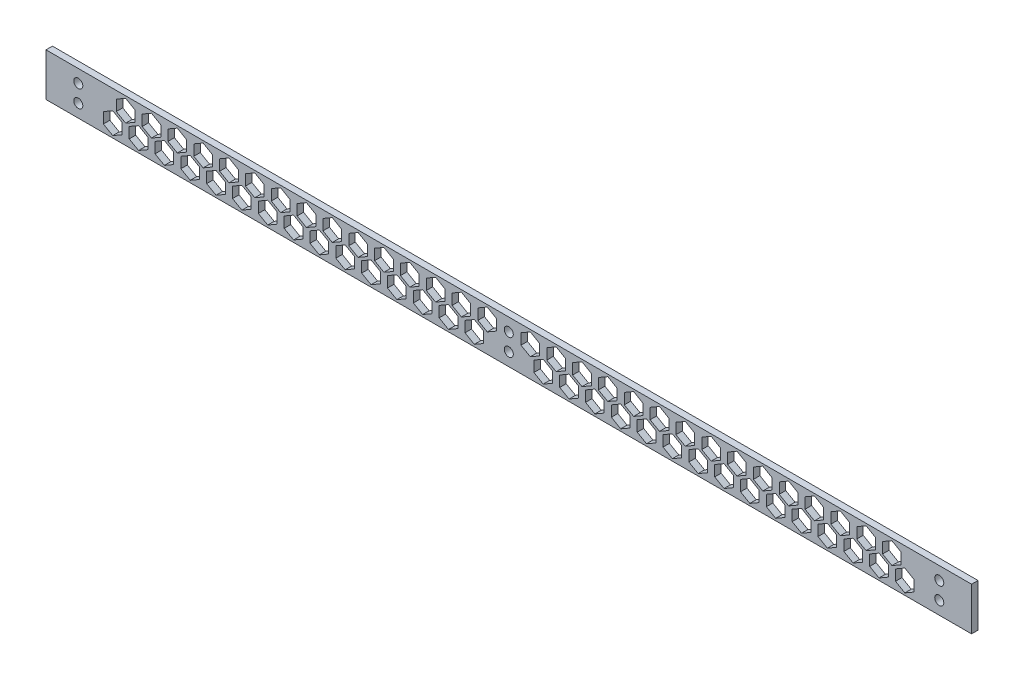
SolidWorks part; units mm, degrees
ref_plane "前视基准面" through (0, 0, 0) normal (0, 0, 1) x (1, 0, 0)
ref_plane "上视基准面" through (0, 0, 0) normal (0, 1, 0) x (1, 0, 0)
ref_plane "右视基准面" through (0, 0, 0) normal (1, 0, 0) x (0, 0, -1)
other "Configuration Table"
sketch "草图2" plane through (0, 0, 0) normal (0, 0, 1) x (1, 0, 0)
  line L0 (0, 42.2596) -> (0, -23.9078) construction
  line L1 (215, -10) -> (-215, -10)
  line L2 (215, -10) -> (215, 10)
  line L3 (215, 10) -> (-215, 10)
  line L4 (-215, -10) -> (-215, 10)
  line L5 (215, -10) -> (-215, 10) construction
  line L6 (215, 10) -> (-215, -10) construction
  line L7 (-28, -9) -> (-23.6699, -6.5)
  line L8 (-10, 9) -> (-14.3301, 6.5)
  line L9 (-14.3301, 6.5) -> (-14.3301, 1.5)
  line L10 (-14.3301, 1.5) -> (-10, -1)
  line L11 (-10, -1) -> (-5.6699, 1.5)
  line L12 (-5.6699, 1.5) -> (-5.6699, 6.5)
  line L13 (-5.6699, 6.5) -> (-10, 9)
  line L14 (-16, -9) -> (-11.6699, -6.5)
  line L15 (-11.6699, -6.5) -> (-11.6699, -1.5)
  line L16 (-11.6699, -1.5) -> (-16, 1)
  line L17 (-16, 1) -> (-20.3301, -1.5)
  line L18 (-20.3301, -1.5) -> (-20.3301, -6.5)
  line L19 (-20.3301, -6.5) -> (-16, -9)
  line L20 (-23.6699, -6.5) -> (-23.6699, -1.5)
  line L21 (-23.6699, -1.5) -> (-28, 1)
  line L22 (-28, 1) -> (-32.3301, -1.5)
  line L23 (-32.3301, -1.5) -> (-32.3301, -6.5)
  line L24 (-32.3301, -6.5) -> (-28, -9)
  line L25 (-22, 9) -> (-26.3301, 6.5)
  line L26 (-26.3301, 6.5) -> (-26.3301, 1.5)
  line L27 (-26.3301, 1.5) -> (-22, -1)
  line L28 (-22, -1) -> (-17.6699, 1.5)
  line L29 (-17.6699, 1.5) -> (-17.6699, 6.5)
  line L30 (-17.6699, 6.5) -> (-22, 9)
  line L31 (-40, -9) -> (-35.6699, -6.5)
  line L32 (-35.6699, -6.5) -> (-35.6699, -1.5)
  line L33 (-35.6699, -1.5) -> (-40, 1)
  line L34 (-40, 1) -> (-44.3301, -1.5)
  line L35 (-44.3301, -1.5) -> (-44.3301, -6.5)
  line L36 (-44.3301, -6.5) -> (-40, -9)
  line L37 (-34, 9) -> (-38.3301, 6.5)
  line L38 (-38.3301, 6.5) -> (-38.3301, 1.5)
  line L39 (-38.3301, 1.5) -> (-34, -1)
  line L40 (-34, -1) -> (-29.6699, 1.5)
  line L41 (-29.6699, 1.5) -> (-29.6699, 6.5)
  line L42 (-29.6699, 6.5) -> (-34, 9)
  line L43 (-52, -9) -> (-47.6699, -6.5)
  line L44 (-47.6699, -6.5) -> (-47.6699, -1.5)
  line L45 (-47.6699, -1.5) -> (-52, 1)
  line L46 (-52, 1) -> (-56.3301, -1.5)
  line L47 (-56.3301, -1.5) -> (-56.3301, -6.5)
  line L48 (-56.3301, -6.5) -> (-52, -9)
  line L49 (-46, 9) -> (-50.3301, 6.5)
  line L50 (-50.3301, 6.5) -> (-50.3301, 1.5)
  line L51 (-50.3301, 1.5) -> (-46, -1)
  line L52 (-46, -1) -> (-41.6699, 1.5)
  line L53 (-41.6699, 1.5) -> (-41.6699, 6.5)
  line L54 (-41.6699, 6.5) -> (-46, 9)
  line L55 (-64, -9) -> (-59.6699, -6.5)
  line L56 (-59.6699, -6.5) -> (-59.6699, -1.5)
  line L57 (-59.6699, -1.5) -> (-64, 1)
  line L58 (-64, 1) -> (-68.3301, -1.5)
  line L59 (-68.3301, -1.5) -> (-68.3301, -6.5)
  line L60 (-68.3301, -6.5) -> (-64, -9)
  line L61 (-58, 9) -> (-62.3301, 6.5)
  line L62 (-62.3301, 6.5) -> (-62.3301, 1.5)
  line L63 (-62.3301, 1.5) -> (-58, -1)
  line L64 (-58, -1) -> (-53.6699, 1.5)
  line L65 (-53.6699, 1.5) -> (-53.6699, 6.5)
  line L66 (-53.6699, 6.5) -> (-58, 9)
  line L67 (-76, -9) -> (-71.6699, -6.5)
  line L68 (-71.6699, -6.5) -> (-71.6699, -1.5)
  line L69 (-71.6699, -1.5) -> (-76, 1)
  line L70 (-76, 1) -> (-80.3301, -1.5)
  line L71 (-80.3301, -1.5) -> (-80.3301, -6.5)
  line L72 (-80.3301, -6.5) -> (-76, -9)
  line L73 (-70, 9) -> (-74.3301, 6.5)
  line L74 (-74.3301, 6.5) -> (-74.3301, 1.5)
  line L75 (-74.3301, 1.5) -> (-70, -1)
  line L76 (-70, -1) -> (-65.6699, 1.5)
  line L77 (-65.6699, 1.5) -> (-65.6699, 6.5)
  line L78 (-65.6699, 6.5) -> (-70, 9)
  line L79 (-88, -9) -> (-83.6699, -6.5)
  line L80 (-83.6699, -6.5) -> (-83.6699, -1.5)
  line L81 (-83.6699, -1.5) -> (-88, 1)
  line L82 (-88, 1) -> (-92.3301, -1.5)
  line L83 (-92.3301, -1.5) -> (-92.3301, -6.5)
  line L84 (-92.3301, -6.5) -> (-88, -9)
  line L85 (-82, 9) -> (-86.3301, 6.5)
  line L86 (-86.3301, 6.5) -> (-86.3301, 1.5)
  line L87 (-86.3301, 1.5) -> (-82, -1)
  line L88 (-82, -1) -> (-77.6699, 1.5)
  line L89 (-77.6699, 1.5) -> (-77.6699, 6.5)
  line L90 (-77.6699, 6.5) -> (-82, 9)
  line L91 (-100, -9) -> (-95.6699, -6.5)
  line L92 (-95.6699, -6.5) -> (-95.6699, -1.5)
  line L93 (-95.6699, -1.5) -> (-100, 1)
  line L94 (-100, 1) -> (-104.3301, -1.5)
  line L95 (-104.3301, -1.5) -> (-104.3301, -6.5)
  line L96 (-104.3301, -6.5) -> (-100, -9)
  line L97 (-94, 9) -> (-98.3301, 6.5)
  line L98 (-98.3301, 6.5) -> (-98.3301, 1.5)
  line L99 (-98.3301, 1.5) -> (-94, -1)
  line L100 (-94, -1) -> (-89.6699, 1.5)
  line L101 (-89.6699, 1.5) -> (-89.6699, 6.5)
  line L102 (-89.6699, 6.5) -> (-94, 9)
  line L103 (-112, -9) -> (-107.6699, -6.5)
  line L104 (-107.6699, -6.5) -> (-107.6699, -1.5)
  line L105 (-107.6699, -1.5) -> (-112, 1)
  line L106 (-112, 1) -> (-116.3301, -1.5)
  line L107 (-116.3301, -1.5) -> (-116.3301, -6.5)
  line L108 (-116.3301, -6.5) -> (-112, -9)
  line L109 (-106, 9) -> (-110.3301, 6.5)
  line L110 (-110.3301, 6.5) -> (-110.3301, 1.5)
  line L111 (-110.3301, 1.5) -> (-106, -1)
  line L112 (-106, -1) -> (-101.6699, 1.5)
  line L113 (-101.6699, 1.5) -> (-101.6699, 6.5)
  line L114 (-101.6699, 6.5) -> (-106, 9)
  line L115 (-124, -9) -> (-119.6699, -6.5)
  line L116 (-119.6699, -6.5) -> (-119.6699, -1.5)
  line L117 (-119.6699, -1.5) -> (-124, 1)
  line L118 (-124, 1) -> (-128.3301, -1.5)
  line L119 (-128.3301, -1.5) -> (-128.3301, -6.5)
  line L120 (-128.3301, -6.5) -> (-124, -9)
  line L121 (-118, 9) -> (-122.3301, 6.5)
  line L122 (-122.3301, 6.5) -> (-122.3301, 1.5)
  line L123 (-122.3301, 1.5) -> (-118, -1)
  line L124 (-118, -1) -> (-113.6699, 1.5)
  line L125 (-113.6699, 1.5) -> (-113.6699, 6.5)
  line L126 (-113.6699, 6.5) -> (-118, 9)
  line L127 (-136, -9) -> (-131.6699, -6.5)
  line L128 (-131.6699, -6.5) -> (-131.6699, -1.5)
  line L129 (-131.6699, -1.5) -> (-136, 1)
  line L130 (-136, 1) -> (-140.3301, -1.5)
  line L131 (-140.3301, -1.5) -> (-140.3301, -6.5)
  line L132 (-140.3301, -6.5) -> (-136, -9)
  line L133 (-130, 9) -> (-134.3301, 6.5)
  line L134 (-134.3301, 6.5) -> (-134.3301, 1.5)
  line L135 (-134.3301, 1.5) -> (-130, -1)
  line L136 (-130, -1) -> (-125.6699, 1.5)
  line L137 (-125.6699, 1.5) -> (-125.6699, 6.5)
  line L138 (-125.6699, 6.5) -> (-130, 9)
  line L139 (-148, -9) -> (-143.6699, -6.5)
  line L140 (-143.6699, -6.5) -> (-143.6699, -1.5)
  line L141 (-143.6699, -1.5) -> (-148, 1)
  line L142 (-148, 1) -> (-152.3301, -1.5)
  line L143 (-152.3301, -1.5) -> (-152.3301, -6.5)
  line L144 (-152.3301, -6.5) -> (-148, -9)
  line L145 (-142, 9) -> (-146.3301, 6.5)
  line L146 (-146.3301, 6.5) -> (-146.3301, 1.5)
  line L147 (-146.3301, 1.5) -> (-142, -1)
  line L148 (-142, -1) -> (-137.6699, 1.5)
  line L149 (-137.6699, 1.5) -> (-137.6699, 6.5)
  line L150 (-137.6699, 6.5) -> (-142, 9)
  line L151 (-160, -9) -> (-155.6699, -6.5)
  line L152 (-155.6699, -6.5) -> (-155.6699, -1.5)
  line L153 (-155.6699, -1.5) -> (-160, 1)
  line L154 (-160, 1) -> (-164.3301, -1.5)
  line L155 (-164.3301, -1.5) -> (-164.3301, -6.5)
  line L156 (-164.3301, -6.5) -> (-160, -9)
  line L157 (-154, 9) -> (-158.3301, 6.5)
  line L158 (-158.3301, 6.5) -> (-158.3301, 1.5)
  line L159 (-158.3301, 1.5) -> (-154, -1)
  line L160 (-154, -1) -> (-149.6699, 1.5)
  line L161 (-149.6699, 1.5) -> (-149.6699, 6.5)
  line L162 (-149.6699, 6.5) -> (-154, 9)
  line L163 (-172, -9) -> (-167.6699, -6.5)
  line L164 (-167.6699, -6.5) -> (-167.6699, -1.5)
  line L165 (-167.6699, -1.5) -> (-172, 1)
  line L166 (-172, 1) -> (-176.3301, -1.5)
  line L167 (-176.3301, -1.5) -> (-176.3301, -6.5)
  line L168 (-176.3301, -6.5) -> (-172, -9)
  line L169 (-166, 9) -> (-170.3301, 6.5)
  line L170 (-170.3301, 6.5) -> (-170.3301, 1.5)
  line L171 (-170.3301, 1.5) -> (-166, -1)
  line L172 (-166, -1) -> (-161.6699, 1.5)
  line L173 (-161.6699, 1.5) -> (-161.6699, 6.5)
  line L174 (-161.6699, 6.5) -> (-166, 9)
  line L175 (-184, -9) -> (-179.6699, -6.5)
  line L176 (-179.6699, -6.5) -> (-179.6699, -1.5)
  line L177 (-179.6699, -1.5) -> (-184, 1)
  line L178 (-184, 1) -> (-188.3301, -1.5)
  line L179 (-188.3301, -1.5) -> (-188.3301, -6.5)
  line L180 (-188.3301, -6.5) -> (-184, -9)
  line L181 (-178, 9) -> (-182.3301, 6.5)
  line L182 (-182.3301, 6.5) -> (-182.3301, 1.5)
  line L183 (-182.3301, 1.5) -> (-178, -1)
  line L184 (-178, -1) -> (-173.6699, 1.5)
  line L185 (-173.6699, 1.5) -> (-173.6699, 6.5)
  line L186 (-173.6699, 6.5) -> (-178, 9)
  line L187 (5.6699, 6.5) -> (10, 9)
  line L188 (5.6699, 1.5) -> (5.6699, 6.5)
  line L189 (10, -1) -> (5.6699, 1.5)
  line L190 (14.3301, 1.5) -> (10, -1)
  line L191 (14.3301, 6.5) -> (14.3301, 1.5)
  line L192 (10, 9) -> (14.3301, 6.5)
  line L193 (20.3301, -6.5) -> (16, -9)
  line L194 (20.3301, -1.5) -> (20.3301, -6.5)
  line L195 (16, 1) -> (20.3301, -1.5)
  line L196 (11.6699, -1.5) -> (16, 1)
  line L197 (11.6699, -6.5) -> (11.6699, -1.5)
  line L198 (16, -9) -> (11.6699, -6.5)
  line L199 (17.6699, 6.5) -> (22, 9)
  line L200 (17.6699, 1.5) -> (17.6699, 6.5)
  line L201 (22, -1) -> (17.6699, 1.5)
  line L202 (26.3301, 1.5) -> (22, -1)
  line L203 (26.3301, 6.5) -> (26.3301, 1.5)
  line L204 (22, 9) -> (26.3301, 6.5)
  line L205 (32.3301, -6.5) -> (28, -9)
  line L206 (32.3301, -1.5) -> (32.3301, -6.5)
  line L207 (28, 1) -> (32.3301, -1.5)
  line L208 (23.6699, -1.5) -> (28, 1)
  line L209 (23.6699, -6.5) -> (23.6699, -1.5)
  line L210 (28, -9) -> (23.6699, -6.5)
  line L211 (29.6699, 6.5) -> (34, 9)
  line L212 (29.6699, 1.5) -> (29.6699, 6.5)
  line L213 (34, -1) -> (29.6699, 1.5)
  line L214 (38.3301, 1.5) -> (34, -1)
  line L215 (38.3301, 6.5) -> (38.3301, 1.5)
  line L216 (34, 9) -> (38.3301, 6.5)
  line L217 (44.3301, -6.5) -> (40, -9)
  line L218 (44.3301, -1.5) -> (44.3301, -6.5)
  line L219 (40, 1) -> (44.3301, -1.5)
  line L220 (35.6699, -1.5) -> (40, 1)
  line L221 (35.6699, -6.5) -> (35.6699, -1.5)
  line L222 (40, -9) -> (35.6699, -6.5)
  line L223 (56.3301, -6.5) -> (52, -9)
  line L224 (56.3301, -1.5) -> (56.3301, -6.5)
  line L225 (52, 1) -> (56.3301, -1.5)
  line L226 (47.6699, -1.5) -> (52, 1)
  line L227 (47.6699, -6.5) -> (47.6699, -1.5)
  line L228 (52, -9) -> (47.6699, -6.5)
  line L229 (41.6699, 6.5) -> (46, 9)
  line L230 (41.6699, 1.5) -> (41.6699, 6.5)
  line L231 (46, -1) -> (41.6699, 1.5)
  line L232 (50.3301, 1.5) -> (46, -1)
  line L233 (50.3301, 6.5) -> (50.3301, 1.5)
  line L234 (46, 9) -> (50.3301, 6.5)
  line L235 (53.6699, 6.5) -> (58, 9)
  line L236 (53.6699, 1.5) -> (53.6699, 6.5)
  line L237 (58, -1) -> (53.6699, 1.5)
  line L238 (62.3301, 1.5) -> (58, -1)
  line L239 (62.3301, 6.5) -> (62.3301, 1.5)
  line L240 (58, 9) -> (62.3301, 6.5)
  line L241 (68.3301, -6.5) -> (64, -9)
  line L242 (68.3301, -1.5) -> (68.3301, -6.5)
  line L243 (64, 1) -> (68.3301, -1.5)
  line L244 (59.6699, -1.5) -> (64, 1)
  line L245 (59.6699, -6.5) -> (59.6699, -1.5)
  line L246 (64, -9) -> (59.6699, -6.5)
  line L247 (80.3301, -6.5) -> (76, -9)
  line L248 (80.3301, -1.5) -> (80.3301, -6.5)
  line L249 (76, 1) -> (80.3301, -1.5)
  line L250 (71.6699, -1.5) -> (76, 1)
  line L251 (71.6699, -6.5) -> (71.6699, -1.5)
  line L252 (76, -9) -> (71.6699, -6.5)
  line L253 (65.6699, 6.5) -> (70, 9)
  line L254 (65.6699, 1.5) -> (65.6699, 6.5)
  line L255 (70, -1) -> (65.6699, 1.5)
  line L256 (74.3301, 1.5) -> (70, -1)
  line L257 (74.3301, 6.5) -> (74.3301, 1.5)
  line L258 (70, 9) -> (74.3301, 6.5)
  line L259 (77.6699, 6.5) -> (82, 9)
  line L260 (77.6699, 1.5) -> (77.6699, 6.5)
  line L261 (82, -1) -> (77.6699, 1.5)
  line L262 (86.3301, 1.5) -> (82, -1)
  line L263 (86.3301, 6.5) -> (86.3301, 1.5)
  line L264 (82, 9) -> (86.3301, 6.5)
  line L265 (92.3301, -6.5) -> (88, -9)
  line L266 (92.3301, -1.5) -> (92.3301, -6.5)
  line L267 (88, 1) -> (92.3301, -1.5)
  line L268 (83.6699, -1.5) -> (88, 1)
  line L269 (83.6699, -6.5) -> (83.6699, -1.5)
  line L270 (88, -9) -> (83.6699, -6.5)
  line L271 (89.6699, 6.5) -> (94, 9)
  line L272 (89.6699, 1.5) -> (89.6699, 6.5)
  line L273 (94, -1) -> (89.6699, 1.5)
  line L274 (98.3301, 1.5) -> (94, -1)
  line L275 (98.3301, 6.5) -> (98.3301, 1.5)
  line L276 (94, 9) -> (98.3301, 6.5)
  line L277 (104.3301, -6.5) -> (100, -9)
  line L278 (104.3301, -1.5) -> (104.3301, -6.5)
  line L279 (100, 1) -> (104.3301, -1.5)
  line L280 (95.6699, -1.5) -> (100, 1)
  line L281 (95.6699, -6.5) -> (95.6699, -1.5)
  line L282 (100, -9) -> (95.6699, -6.5)
  line L283 (101.6699, 6.5) -> (106, 9)
  line L284 (101.6699, 1.5) -> (101.6699, 6.5)
  line L285 (106, -1) -> (101.6699, 1.5)
  line L286 (110.3301, 1.5) -> (106, -1)
  line L287 (110.3301, 6.5) -> (110.3301, 1.5)
  line L288 (106, 9) -> (110.3301, 6.5)
  line L289 (116.3301, -6.5) -> (112, -9)
  line L290 (116.3301, -1.5) -> (116.3301, -6.5)
  line L291 (112, 1) -> (116.3301, -1.5)
  line L292 (107.6699, -1.5) -> (112, 1)
  line L293 (107.6699, -6.5) -> (107.6699, -1.5)
  line L294 (112, -9) -> (107.6699, -6.5)
  line L295 (113.6699, 6.5) -> (118, 9)
  line L296 (113.6699, 1.5) -> (113.6699, 6.5)
  line L297 (118, -1) -> (113.6699, 1.5)
  line L298 (122.3301, 1.5) -> (118, -1)
  line L299 (122.3301, 6.5) -> (122.3301, 1.5)
  line L300 (118, 9) -> (122.3301, 6.5)
  line L301 (128.3301, -6.5) -> (124, -9)
  line L302 (128.3301, -1.5) -> (128.3301, -6.5)
  line L303 (124, 1) -> (128.3301, -1.5)
  line L304 (119.6699, -1.5) -> (124, 1)
  line L305 (119.6699, -6.5) -> (119.6699, -1.5)
  line L306 (124, -9) -> (119.6699, -6.5)
  line L307 (125.6699, 6.5) -> (130, 9)
  line L308 (125.6699, 1.5) -> (125.6699, 6.5)
  line L309 (130, -1) -> (125.6699, 1.5)
  line L310 (134.3301, 1.5) -> (130, -1)
  line L311 (134.3301, 6.5) -> (134.3301, 1.5)
  line L312 (130, 9) -> (134.3301, 6.5)
  line L313 (140.3301, -6.5) -> (136, -9)
  line L314 (140.3301, -1.5) -> (140.3301, -6.5)
  line L315 (136, 1) -> (140.3301, -1.5)
  line L316 (131.6699, -1.5) -> (136, 1)
  line L317 (131.6699, -6.5) -> (131.6699, -1.5)
  line L318 (136, -9) -> (131.6699, -6.5)
  line L319 (137.6699, 6.5) -> (142, 9)
  line L320 (137.6699, 1.5) -> (137.6699, 6.5)
  line L321 (142, -1) -> (137.6699, 1.5)
  line L322 (146.3301, 1.5) -> (142, -1)
  line L323 (146.3301, 6.5) -> (146.3301, 1.5)
  line L324 (142, 9) -> (146.3301, 6.5)
  line L325 (152.3301, -6.5) -> (148, -9)
  line L326 (152.3301, -1.5) -> (152.3301, -6.5)
  line L327 (148, 1) -> (152.3301, -1.5)
  line L328 (143.6699, -1.5) -> (148, 1)
  line L329 (143.6699, -6.5) -> (143.6699, -1.5)
  line L330 (148, -9) -> (143.6699, -6.5)
  line L331 (149.6699, 6.5) -> (154, 9)
  line L332 (149.6699, 1.5) -> (149.6699, 6.5)
  line L333 (154, -1) -> (149.6699, 1.5)
  line L334 (158.3301, 1.5) -> (154, -1)
  line L335 (158.3301, 6.5) -> (158.3301, 1.5)
  line L336 (154, 9) -> (158.3301, 6.5)
  line L337 (164.3301, -6.5) -> (160, -9)
  line L338 (164.3301, -1.5) -> (164.3301, -6.5)
  line L339 (160, 1) -> (164.3301, -1.5)
  line L340 (155.6699, -1.5) -> (160, 1)
  line L341 (155.6699, -6.5) -> (155.6699, -1.5)
  line L342 (160, -9) -> (155.6699, -6.5)
  line L343 (161.6699, 6.5) -> (166, 9)
  line L344 (161.6699, 1.5) -> (161.6699, 6.5)
  line L345 (166, -1) -> (161.6699, 1.5)
  line L346 (170.3301, 1.5) -> (166, -1)
  line L347 (170.3301, 6.5) -> (170.3301, 1.5)
  line L348 (166, 9) -> (170.3301, 6.5)
  line L349 (176.3301, -6.5) -> (172, -9)
  line L350 (176.3301, -1.5) -> (176.3301, -6.5)
  line L351 (172, 1) -> (176.3301, -1.5)
  line L352 (167.6699, -1.5) -> (172, 1)
  line L353 (167.6699, -6.5) -> (167.6699, -1.5)
  line L354 (172, -9) -> (167.6699, -6.5)
  line L355 (188.3301, -6.5) -> (184, -9)
  line L356 (188.3301, -1.5) -> (188.3301, -6.5)
  line L357 (184, 1) -> (188.3301, -1.5)
  line L358 (179.6699, -1.5) -> (184, 1)
  line L359 (179.6699, -6.5) -> (179.6699, -1.5)
  line L360 (184, -9) -> (179.6699, -6.5)
  line L361 (173.6699, 6.5) -> (178, 9)
  line L362 (173.6699, 1.5) -> (173.6699, 6.5)
  line L363 (178, -1) -> (173.6699, 1.5)
  line L364 (182.3301, 1.5) -> (178, -1)
  line L365 (182.3301, 6.5) -> (182.3301, 1.5)
  line L366 (178, 9) -> (182.3301, 6.5)
  circle A0 centre (0, 4) radius 2.1
  circle A1 centre (0, -4) radius 2.1
  circle A2 centre (200, 4) radius 2.1
  circle A3 centre (200, -4) radius 2.1
  circle A4 centre (-200, 4) radius 2.1
  circle A5 centre (-200, -4) radius 2.1
  circle A6 centre (-10, 4) radius 4.3301 construction
  circle A7 centre (-16, -4) radius 4.3301 construction
  point P0 (0, 0)
  dimension "D3" = 4.2
  dimension "D1" = 20
  dimension "D2" = 430
  dimension "D4" = 8
  dimension "D5" = 4
  dimension "D8" = 5
  dimension "D9" = 6
  dimension "D10" = 10
  dimension "D11" = 5
  dimension "D12" = 6
  dimension "D13" = 16
  dimension "D6" = 2
  dimension "D7" = 2
  dimension "D14" = 15
extrude "凸台-拉伸1" add sketch "草图2" along normal blind 3
